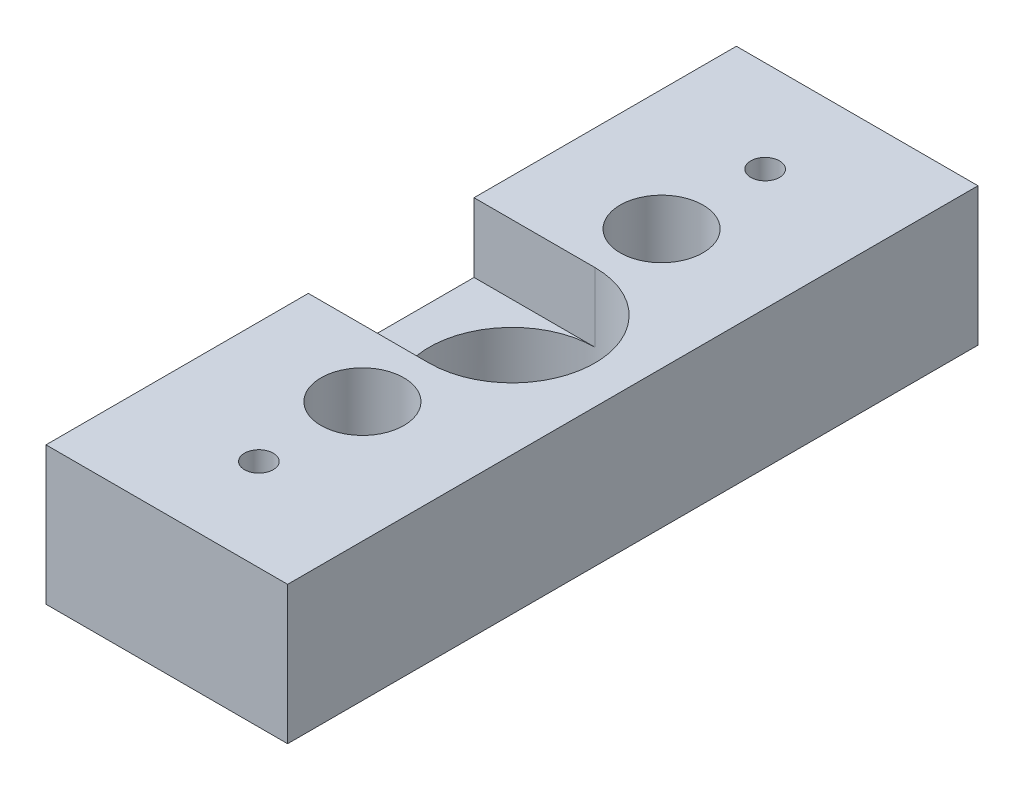
SolidWorks part; units mm, degrees
ref_plane "Front Plane" through (0, 0, 0) normal (0, 0, 1) x (1, 0, 0)
ref_plane "Top Plane" through (0, 0, 0) normal (0, 1, 0) x (1, 0, 0)
ref_plane "Right Plane" through (0, 0, 0) normal (1, 0, 0) x (0, 0, -1)
sketch "Sketch1" plane through (0, 0, 0) normal (0, 1, 0) x (1, 0, 0)
  line L2 (6, 2) -> (6, -13)
  line L3 (6, -13) -> (-4.5, -13)
  line L5 (1.5, 2) -> (-4.5, 2)
  line L6 (-4.5, 2) -> (-4.5, -2)
  line L11 (-4.5, -2) -> (-4.5, -13)
  line L12 (1.5, 2) -> (6, 2)
  point P0 (0, 0)
  dimension "D2" = 10.5
  dimension "D3" = 15
extrude "Boss-Extrude1" add sketch "Sketch1" along normal blind 6
hole_wizard "CSK SLOT for M1.6 Countersunk Flat Head Screw1" positions "Sketch2" profile "Sketch3" size "M1.6" standard "ISO" slot yes end condition through all
sketch "Sketch2" plane through (0, 6, 0) normal (0, 1, 0) x (1, 0, 0)
  line L2 (0.75, 2) -> (0.75, -4.5)
  line L5 (6, 2) -> (-4.5, 2) construction
  point P0 (0.75, -4.5)
  point P19 (0.75, 2)
  dimension "D1" = 6.5
sketch "Sketch3" plane through (0.75, 6, 4.5) normal (1, 0, 0) x (0, 0, 1)
  line L0 (0, 0) -> (0, 6)
  line L1 (0, 6) -> (0.9, 6)
  line L2 (0.9, 6) -> (0.9, 4.9)
  line L3 (0.9, 4.9) -> (1.8, 4)
  line L4 (1.8, 4) -> (1.8, 0)
  line L6 (1.8, 0) -> (0, 0)
  line L7 (-0.9, 4.9) -> (-1.8, 4) construction
  line L11 (0, -6.35) -> (0, 107.95) construction
  dimension "Thru Hole Dia." = 1.8
  dimension "Thru Hole Depth" = 6
  dimension "C'Sink Dia." = 3.6
  dimension "C'Sink Angle" = 90
  dimension "Head Clearance" = 4
ref_plane "Plane1" through (0, 0, -2) normal (0, 0, -1) x (-1, 0, 0)
hole_wizard "M1.6 Tapped Hole1" positions "Sketch4" profile "Sketch5" tap size "M1.6" standard "ISO" end condition through all
sketch "Sketch4" plane through (0, 6, 0) normal (0, 1, 0) x (1, 0, 0)
  line L0 (-4.5, -13) -> (6, -13) construction
  line L1 (0.75, -13) -> (0.75, -9)
  point P0 (0.75, -9)
  dimension "D1" = 4
sketch "Sketch5" plane through (0.75, 6, 9) normal (1, 0, 0) x (0, 0, 1)
  line L0 (0, 0) -> (0, 6)
  line L1 (0, 6) -> (0.625, 6)
  line L2 (0.625, 6) -> (0.625, 0)
  line L5 (0.625, 0) -> (0, 0)
  line L11 (0, -6.35) -> (0, 107.95) construction
  dimension "Thru Tap Drill Dia." = 1.25
  dimension "Thru Tap Drill Depth" = 6
cosmetic thread "Hole Thread1" parameters "D2"=1.6
mirror "Mirror1" about plane through (0, 0, -2) normal (0, 0, -1) of "CSK SLOT for M1.6 Countersunk Flat Head Screw1", "Boss-Extrude1", "M1.6 Tapped Hole1"
cosmetic thread "Hole Thread2" parameters "D2"=1.6
sketch "Sketch6" plane through (0, 6, 0) normal (0, 1, 0) x (1, 0, 0)
  line L0 (-4.5, 2) -> (6, 2) construction
  line L1 (-4.5, 17) -> (-4.5, -13) construction
  line L3 (6, -13) -> (6, 17) construction
  circle A0 centre (0.75, 2) radius 3.6
  dimension "D1" = 7.2
extrude "Cut-Extrude1" cut sketch "Sketch6" against normal through all
sketch "Sketch7" plane through (0, 6, 0) normal (0, 1, 0) x (1, 0, 0)
  line L0 (0.75, 5.6) -> (-4.5, 5.6)
  line L1 (-4.5, 17) -> (-4.5, -13) construction
  line L2 (-4.5, 5.6) -> (-4.5, -1.6)
  line L3 (-4.5, -1.6) -> (0.75, -1.6)
  line L4 (0.75, -1.6) -> (0.75, 5.6)
  circle A0 centre (0.75, 2) radius 3.6 construction
extrude "Cut-Extrude2" cut sketch "Sketch7" against normal blind 3
